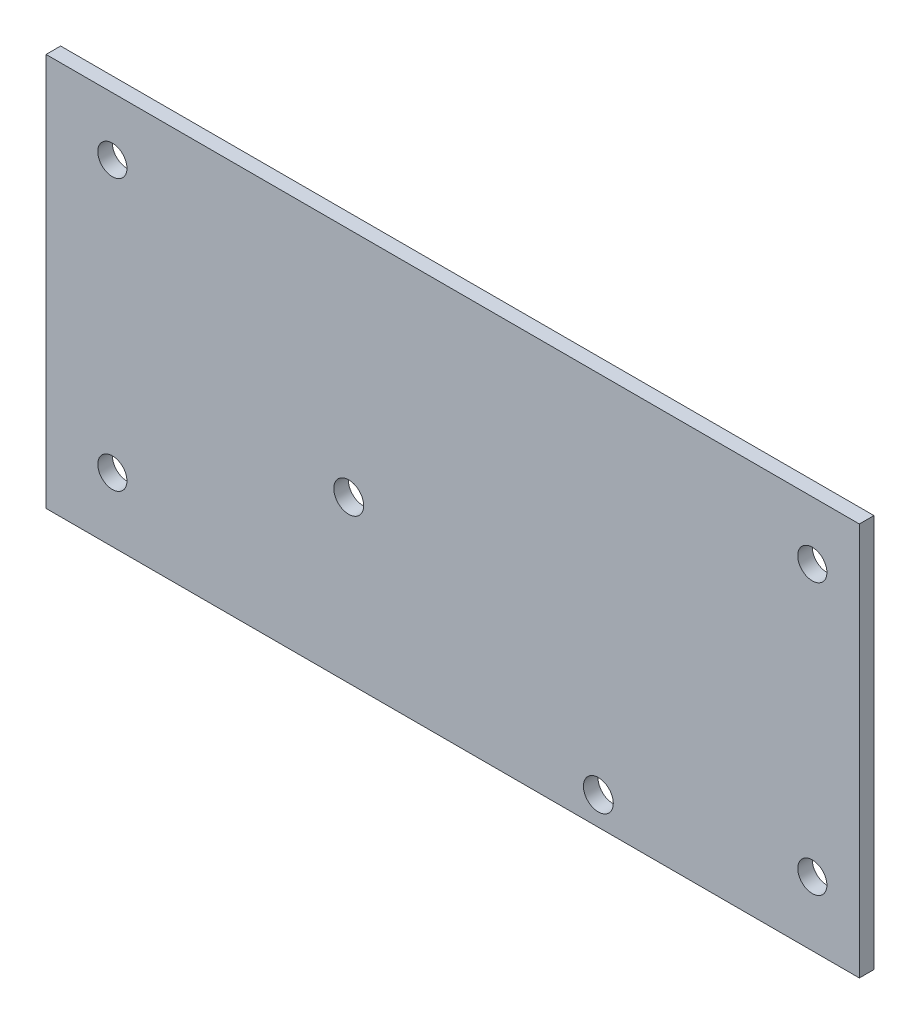
SolidWorks part; units mm, degrees
ref_plane "Front Plane" through (0, 0, 0) normal (0, 0, 1) x (1, 0, 0)
ref_plane "Top Plane" through (0, 0, 0) normal (0, 1, 0) x (1, 0, 0)
ref_plane "Right Plane" through (0, 0, 0) normal (1, 0, 0) x (0, 0, -1)
sketch "Sketch1" plane through (0, 0, 0) normal (0, 0, 1) x (1, 0, 0)
  line L0 (-160.8839, 244.2817) -> (-110.0839, 244.2817) construction
  line L1 (-65.958, 307.4989) -> (-243.0357, 307.4989)
  line L2 (-65.958, 307.4989) -> (-65.958, 221.8871)
  line L3 (-65.958, 221.8871) -> (-243.0357, 221.8871)
  line L4 (-243.0357, 307.4989) -> (-243.0357, 221.8871)
  line L5 (-160.8839, 295.0817) -> (-160.8839, 244.2817) construction
  line L6 (-110.0839, 244.2817) -> (-110.0839, 295.0817) construction
  circle A0 centre (-76.2, 294.8214) radius 3.175
  circle A1 centre (-76.2, 235.8571) radius 3.175
  circle A2 centre (-228.6, 294.8214) radius 3.175
  circle A3 centre (-228.6, 235.8571) radius 3.175
  circle A4 centre (-122.7839, 228.0257) radius 3.2512
  circle A5 centre (-177.1399, 256.9817) radius 3.2512
  dimension "D1" = 6.35
  dimension "D2" = 6.35
  dimension "D3" = 6.35
  dimension "D4" = 6.35
  dimension "D9" = 6.5024
  dimension "D5" = 10.242
  dimension "D6" = 13.97
  dimension "D7" = 14.4357
  dimension "D8" = 12.6774
  dimension "D10" = 16.256
  dimension "D11" = 16.256
  dimension "D12" = 12.7
  dimension "D13" = 12.7
extrude "Boss-Extrude1" add sketch "Sketch1" along normal blind 3.175
equation "\"80/20 to Center Hole\"= .64in"
equation "\"80/20 from Edge\"= 0.5in"
equation "\"D10@Sketch1\"=\"80/20 to Center Hole\""
equation "\"D11@Sketch1\"=\"80/20 to Center Hole\""
equation "\"D12@Sketch1\"=\"80/20 from Edge\""
equation "\"D13@Sketch1\"=\"80/20 from Edge\""
